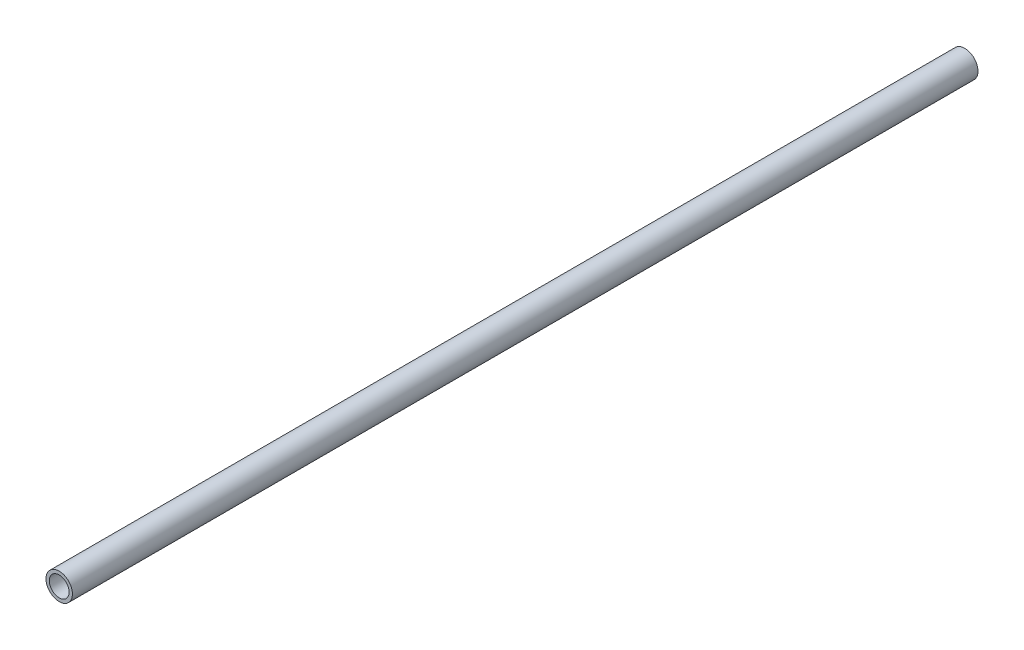
SolidWorks part; units mm, degrees
ref_plane "Plan de face" through (0, 0, 0) normal (0, 0, 1) x (1, 0, 0)
ref_plane "Plan de dessus" through (0, 0, 0) normal (0, 1, 0) x (1, 0, 0)
ref_plane "Plan de droite" through (0, 0, 0) normal (1, 0, 0) x (0, 0, -1)
sketch "Esquisse1" plane through (0, 0, 0) normal (0, 0, 1) x (1, 0, 0)
  circle A0 centre (0, 0) radius 2
extrude "Extru.-Mince1" add sketch "Esquisse1" along normal blind 137 thin thin type one direction reverse wall 0.5
